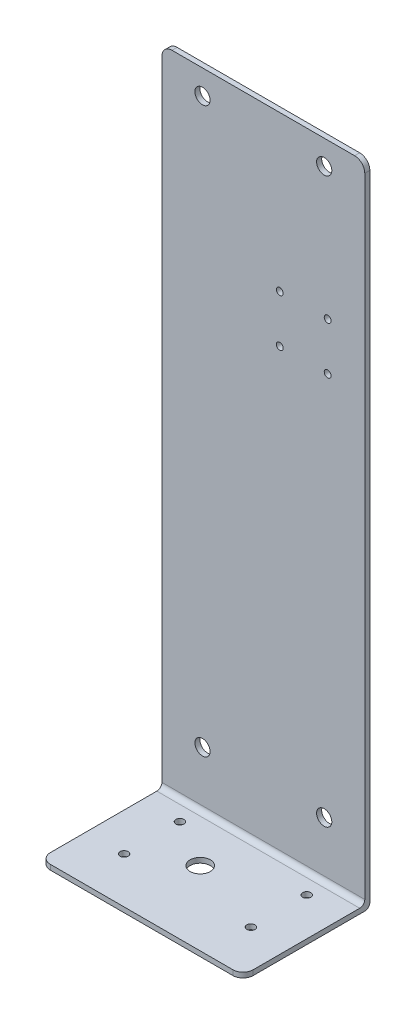
SolidWorks part; units mm, degrees
ref_plane "Front Plane" through (0, 0, 0) normal (0, 0, 1) x (1, 0, 0)
ref_plane "Top Plane" through (0, 0, 0) normal (0, 1, 0) x (1, 0, 0)
ref_plane "Right Plane" through (0, 0, 0) normal (1, 0, 0) x (0, 0, -1)
sketch "Sketch2" plane through (0, 0, 0) normal (0, 0, 1) x (1, 0, 0)
  line L1 (-63.5, -203.2) -> (63.5, -203.2)
  line L2 (-63.5, -203.2) -> (-63.5, 203.2)
  line L3 (-63.5, 203.2) -> (63.5, 203.2)
  line L4 (63.5, -203.2) -> (63.5, 203.2)
  line L5 (-63.5, -203.2) -> (63.5, 203.2) construction
  line L6 (-63.5, 203.2) -> (63.5, -203.2) construction
  point P0 (0, 0)
  dimension "D1" = 127
  dimension "D2" = 406.4
extrude "Boss-Extrude1" add sketch "Sketch2" along normal blind 3.175
sketch "Sketch3" plane through (0, 0, 3.175) normal (0, 0, 1) x (1, 0, 0)
  line L0 (63.5, -203.2) -> (63.5, 203.2) construction
  line L1 (-63.5, -203.2) -> (63.5, -203.2)
  line L2 (-63.5, -203.2) -> (-63.5, -200.025)
  line L3 (-63.5, -200.025) -> (63.5, -200.025)
  line L4 (63.5, -203.2) -> (63.5, -200.025)
  dimension "D1" = 3.175
extrude "Boss-Extrude2" add sketch "Sketch3" along normal blind 76.2
fillet "Fillet1" radius 3.175 2 edges at (0, -203.2, 0) (0, -200.025, 3.175)
fillet "Fillet2" radius 6.35 4 edges at (63.5, -201.6125, 79.375) (-63.5, -201.6125, 79.375) (63.5, 203.2, 1.5875) (-63.5, 203.2, 1.5875)
sketch "Sketch4" plane through (0, -200.025, 0) normal (0, 1, 0) x (1, 0, 0)
  line L0 (63.5, -73.025) -> (63.5, -6.35) construction
  line L1 (57.15, -79.375) -> (-57.15, -79.375) construction
  circle A0 centre (-9.525, -33.175) radius 6.35
  circle A1 centre (-39.6875, -15.7125) radius 2.54
  circle A2 centre (-39.6875, -50.6375) radius 2.54
  circle A3 centre (39.6875, -15.7125) radius 2.54
  circle A4 centre (39.6875, -50.6375) radius 2.54
  dimension "D7" = 5.08
  dimension "D8" = 12.7
  dimension "D1" = 23.8125
  dimension "D2" = 28.7375
  dimension "D3" = 103.1875
  dimension "D4" = 73.025
  dimension "D5" = 46.2
  dimension "D6" = 63.6625
extrude "Cut-Extrude1" cut sketch "Sketch4" against normal through all
sketch "Sketch5" plane through (0, 0, 3.175) normal (0, 0, 1) x (1, 0, 0)
  line L0 (63.5, -196.85) -> (63.5, 196.85) construction
  line L1 (57.15, 203.2) -> (-57.15, 203.2) construction
  circle A0 centre (10.273, 76.475) radius 2.15
  circle A1 centre (40.273, 76.475) radius 2.15
  circle A2 centre (40.273, 106.175) radius 2.15
  circle A3 centre (10.273, 106.175) radius 2.15
  circle A4 centre (-38.1, 187.96) radius 4.7625
  circle A5 centre (38.1, 187.96) radius 4.7625
  circle A6 centre (-38.1, -165.1) radius 4.7625
  circle A7 centre (38.1, -165.1) radius 4.7625
  point P2 (0, 0)
  point P5 (0, 0)
  dimension "D1" = 4.3
  dimension "D5" = 126.725
  dimension "D8" = 9.525
  dimension "D6" = 101.6
  dimension "D11" = 15.24
  dimension "D2" = 23.227
  dimension "D3" = 53.227
  dimension "D4" = 97.025
  dimension "D7" = 368.3
  dimension "D9" = 25.4
  dimension "D10" = 25.4
  dimension "D12" = 101.6
extrude "Cut-Extrude2" cut sketch "Sketch5" against normal through all
